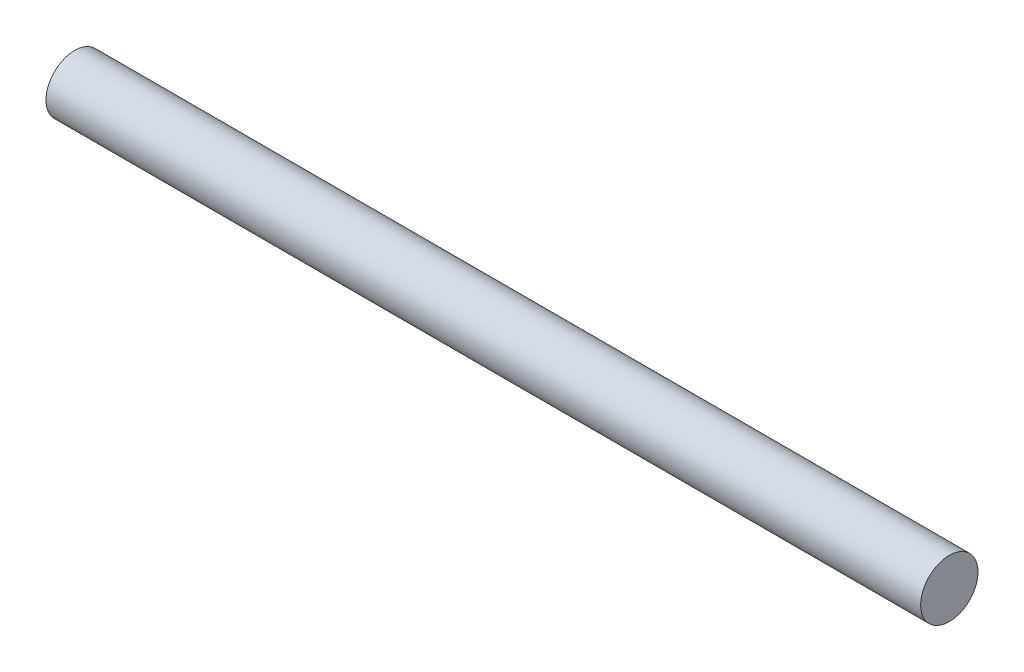
SolidWorks part; units mm, degrees
material "AISI Type A2 Tool Steel"
ref_plane "Front Plane" through (0, 0, 0) normal (0, 0, 1) x (1, 0, 0)
ref_plane "Top Plane" through (0, 0, 0) normal (0, 1, 0) x (1, 0, 0)
ref_plane "Right Plane" through (0, 0, 0) normal (1, 0, 0) x (0, 0, -1)
other "Bounding Box"
ref_plane "Default Plane" through (-8.9266, -12.7485, 0) normal (-0.1736, 0.9848, 0) x (0.9848, 0.1736, 0)
sketch "Sketch1" plane through (0, 0, 0) normal (1, 0, 0) x (0, 0, -1)
  circle A0 centre (0, 0) radius 2.5
  dimension "D1" = 5
extrude "Boss-Extrude1" add sketch "Sketch1" along normal mid plane 76.2
